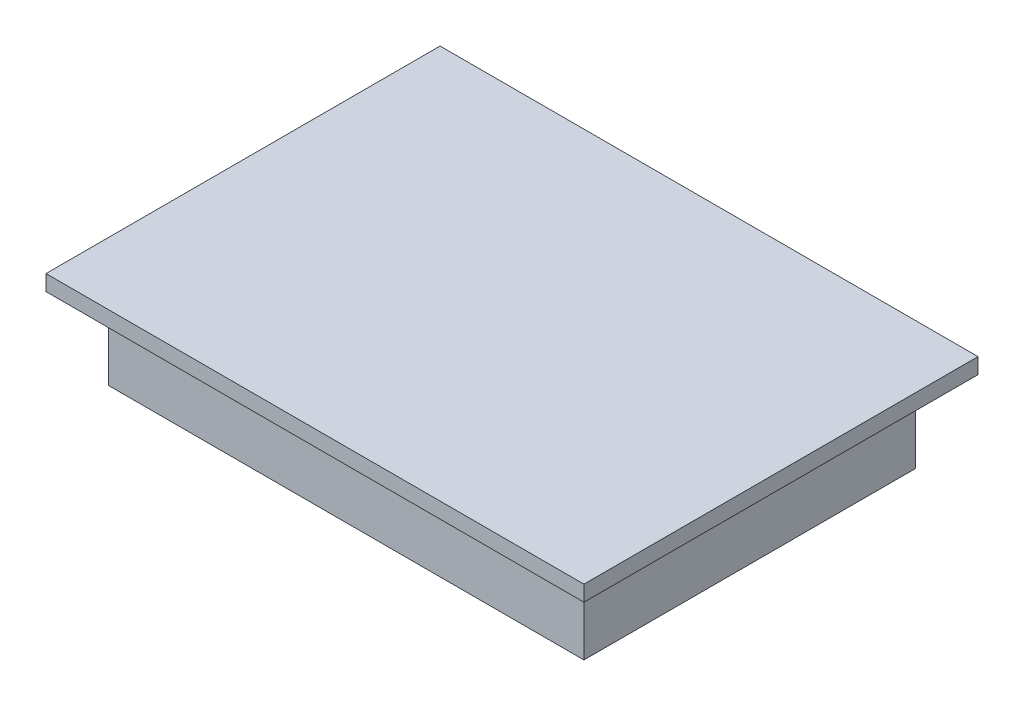
SolidWorks part; units mm, degrees
ref_plane "前视基准面" through (0, 0, 0) normal (0, 0, 1) x (1, 0, 0)
ref_plane "上视基准面" through (0, 0, 0) normal (0, 1, 0) x (1, 0, 0)
ref_plane "右视基准面" through (0, 0, 0) normal (1, 0, 0) x (0, 0, -1)
sketch "草图1" plane through (0, 0, 0) normal (0, 1, 0) x (1, 0, 0)
  line L1 (-38, -26.5) -> (38, -26.5)
  line L2 (-38, -26.5) -> (-38, 26.5)
  line L3 (-38, 26.5) -> (38, 26.5)
  line L4 (38, -26.5) -> (38, 26.5)
  line L5 (-38, -26.5) -> (38, 26.5) construction
  line L6 (-38, 26.5) -> (38, -26.5) construction
  point P0 (0, 0)
  dimension "D1" = 76
  dimension "D2" = 53
extrude "凸台-拉伸1" add sketch "草图1" along normal blind 13
sketch "草图2" plane through (0, 13, 0) normal (0, 1, 0) x (1, 0, 0)
  line L1 (-43, -31.5) -> (43, -31.5)
  line L2 (-43, -31.5) -> (-43, 31.5)
  line L3 (-43, 31.5) -> (43, 31.5)
  line L4 (43, -31.5) -> (43, 31.5)
  line L5 (-43, -31.5) -> (43, 31.5) construction
  line L6 (-43, 31.5) -> (43, -31.5) construction
  point P0 (0, 0)
  dimension "D1" = 86
  dimension "D2" = 63
extrude "凸台-拉伸2" add sketch "草图2" along normal blind 2.5
